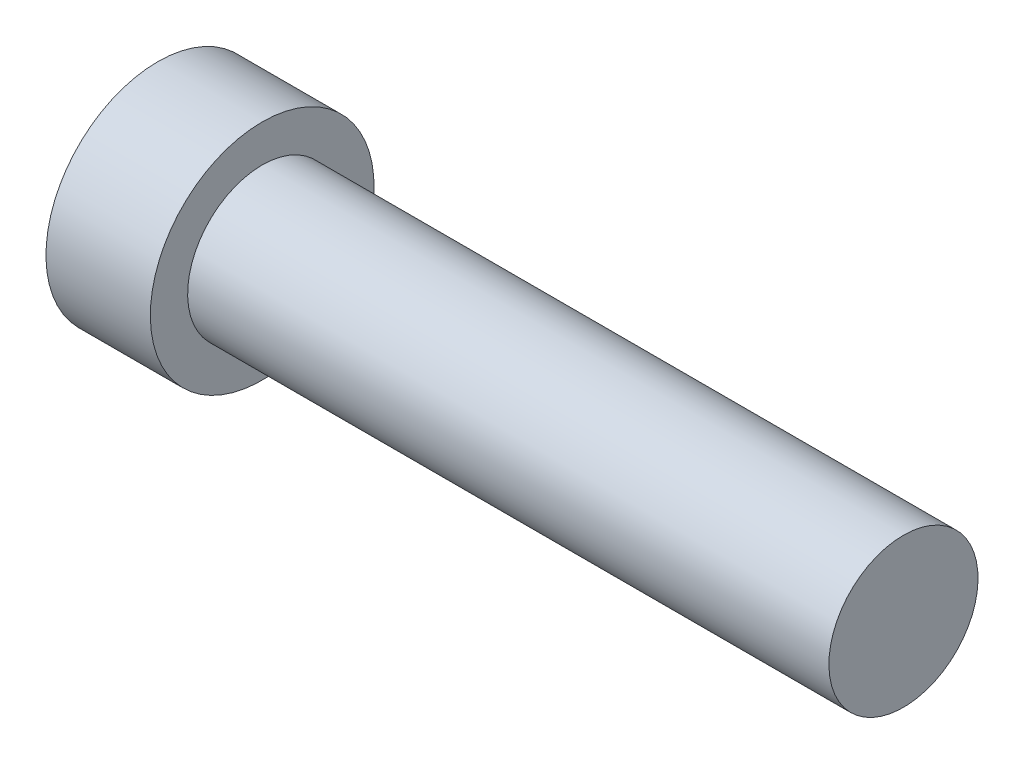
SolidWorks part; units mm, degrees
ref_plane "Front Plane" through (0, 0, 0) normal (0, 0, 1) x (1, 0, 0)
ref_plane "Top Plane" through (0, 0, 0) normal (0, 1, 0) x (1, 0, 0)
ref_plane "Right Plane" through (0, 0, 0) normal (1, 0, 0) x (0, 0, -1)
sketch "Sketch1" plane through (0, 0, 0) normal (0, 0, 1) x (1, 0, 0)
  line L0 (0, 0) -> (0, 7.5)
  line L1 (0, 7.5) -> (7, 7.5)
  line L2 (7, 7.5) -> (7, 0)
  line L3 (7, 0) -> (0, 0)
  line L4 (7, 5) -> (50, 5)
  line L5 (50, 5) -> (50, 0)
  line L6 (50, 0) -> (7, 0)
  dimension "D1" = 7
  dimension "D2" = 50
  dimension "D3" = 7.5
  dimension "D4" = 5
revolve "Revolve1" add sketch "Sketch1" angle 360 about L6
